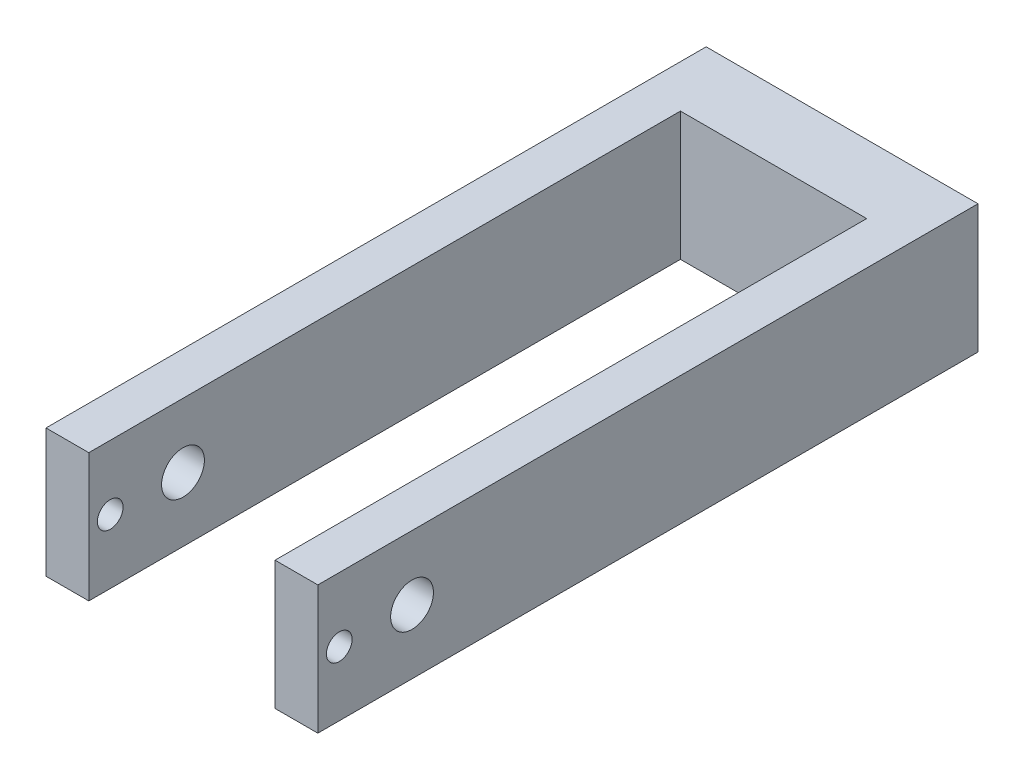
SolidWorks part; units mm, degrees
ref_plane "Front Plane" through (0, 0, 0) normal (0, 0, 1) x (1, 0, 0)
ref_plane "Top Plane" through (0, 0, 0) normal (0, 1, 0) x (1, 0, 0)
ref_plane "Right Plane" through (0, 0, 0) normal (1, 0, 0) x (0, 0, -1)
sketch "Sketch1" plane through (0, 0, 0) normal (0, 0, 1) x (1, 0, 0)
  line L0 (-16.8014, 8.169) -> (14.9486, 8.169)
  line L1 (14.9486, 8.169) -> (14.9486, -6.831)
  line L2 (14.9486, -6.831) -> (-16.8014, -6.831)
  line L3 (-16.8014, -6.831) -> (-16.8014, 8.169)
  dimension "D1" = 31.75
  dimension "D2" = 15
extrude "Boss-Extrude1" add sketch "Sketch1" along normal blind 8
sketch "Sketch2" plane through (0, 0, 8) normal (0, 0, 1) x (1, 0, 0)
  line L0 (-16.8014, 8.169) -> (-11.8014, 8.169)
  line L1 (14.9486, 8.169) -> (-16.8014, 8.169) construction
  line L2 (-11.8014, 8.169) -> (-11.8014, -6.831)
  line L3 (-16.8014, -6.831) -> (14.9486, -6.831) construction
  line L4 (-11.8014, -6.831) -> (-16.8014, -6.831)
  line L5 (-16.8014, -6.831) -> (-16.8014, 8.169)
  line L6 (14.9486, 8.169) -> (9.9486, 8.169)
  line L7 (9.9486, 8.169) -> (9.9486, -6.831)
  line L8 (9.9486, -6.831) -> (14.9486, -6.831)
  line L9 (14.9486, -6.831) -> (14.9486, 8.169)
  dimension "D1" = 5
  dimension "D2" = 5
extrude "Boss-Extrude2" add sketch "Sketch2" along normal blind 69.1
sketch "Sketch3" plane through (14.9486, 0, 0) normal (1, 0, 0) x (0, 0, -1)
  line L0 (-77.1, -6.831) -> (-77.1, 8.169) construction
  circle A0 centre (-66.1, 0.669) radius 2.5
  dimension "D1" = 5
  dimension "D2" = 11
extrude "Cut-Extrude1" cut sketch "Sketch3" against normal blind 69.1
sketch "Sketch4" plane through (0, 0, 0) normal (0, 0, -1) x (-1, 0, 0)
  circle A0 centre (0.9264, 0.669) radius 4
  circle A1 centre (0.9264, 0.669) radius 2
  dimension "D1" = 8
  dimension "D2" = 4
extrude "Cut-Extrude3" cut sketch "Sketch4" against normal blind 4
sketch "Sketch5" plane through (0, -6.831, 0) normal (0, -1, 0) x (1, 0, 0)
  line L0 (-0.9264, 0) -> (-0.9264, 8) construction
  line L1 (-16.8014, 0) -> (14.9486, 0) construction
  line L2 (-11.8014, 8) -> (9.9486, 8) construction
  circle A0 centre (-0.9264, 4) radius 1.5
  point P9 (-0.9264, 4)
  dimension "D1" = 3
extrude "Cut-Extrude4" cut sketch "Sketch5" against normal blind 3
sketch "Sketch6" plane through (14.9486, 0, 0) normal (1, 0, 0) x (0, 0, -1)
  line L0 (-77.1, -6.831) -> (-77.1, 8.169) construction
  circle A0 centre (-74.6, 0.669) radius 1.5
  dimension "D1" = 3
  dimension "D2" = 2.5
extrude "Cut-Extrude5" cut sketch "Sketch6" against normal blind 37
